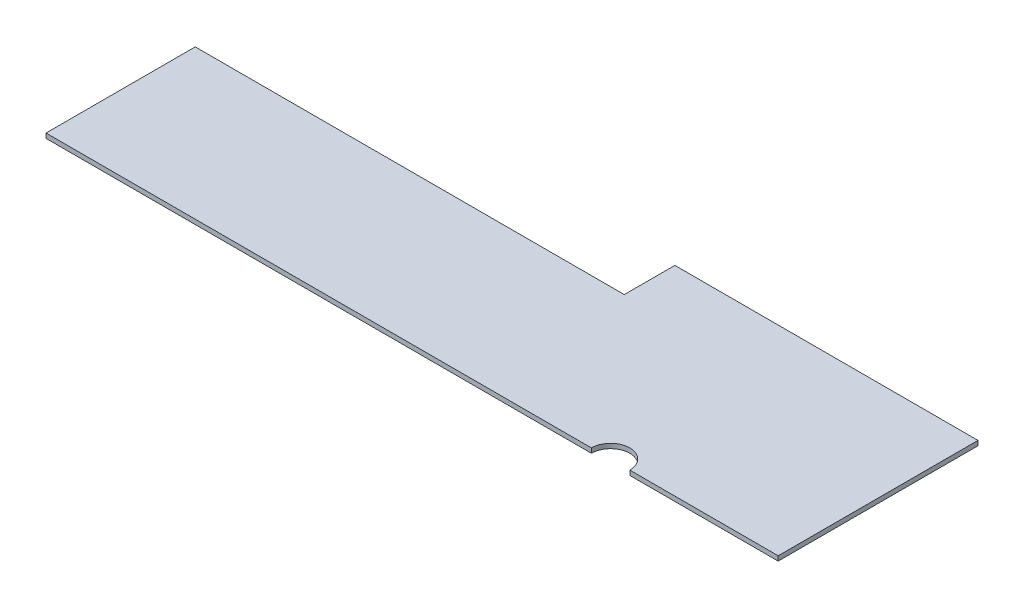
SolidWorks part; units mm, degrees
material "Custom Plastic"
ref_plane "X-Y Datum" through (0, 0, 0) normal (0, 0, 1) x (1, 0, 0)
ref_plane "X-Z Datum" through (0, 0, 0) normal (0, 1, 0) x (1, 0, 0)
ref_plane "Y-Z Datum" through (0, 0, 0) normal (1, 0, 0) x (0, 0, -1)
ref_plane "Plane2" through (0, 0, 0) normal (0, 1, 0) x (1, 0, 0)
sketch "Sketch1" plane through (0, 0, 0) normal (0, 1, 0) x (1, 0, 0)
  line L1 (1020.4196, -384.6687) -> (1017.2446, -384.6687)
  line L3 (521.9446, -419.1) -> (525.1196, -419.1)
  line L4 (1017.2446, -384.6687) -> (814.0446, -384.6687)
  line L5 (814.0446, -384.6687) -> (814.0446, -419.1)
  line L6 (814.0446, -419.1) -> (521.9446, -419.1)
  line L8 (521.9446, -520.7) -> (525.1196, -520.7)
  line L9 (521.9446, -419.1) -> (521.9446, -520.7)
  line L10 (1020.4196, -384.6687) -> (1020.4196, -520.7)
  line L11 (1020.4196, -520.7) -> (525.1196, -520.7)
  circle A0 centre (906.3228, -520.7) radius 13.081
  dimension "D1" = 26.162
  dimension "D2" = 495.3
  dimension "D3" = 136.0313
  dimension "D4" = 3.175
  dimension "D5" = 203.2
  dimension "D6" = 101.6
  dimension "D7" = 292.1
extrude "Boss-Extrude1" add sketch "Sketch1" along normal mid plane 3.175 contours A0 L11 L10 L1 L4 L5 L6 L3 L9 L8
